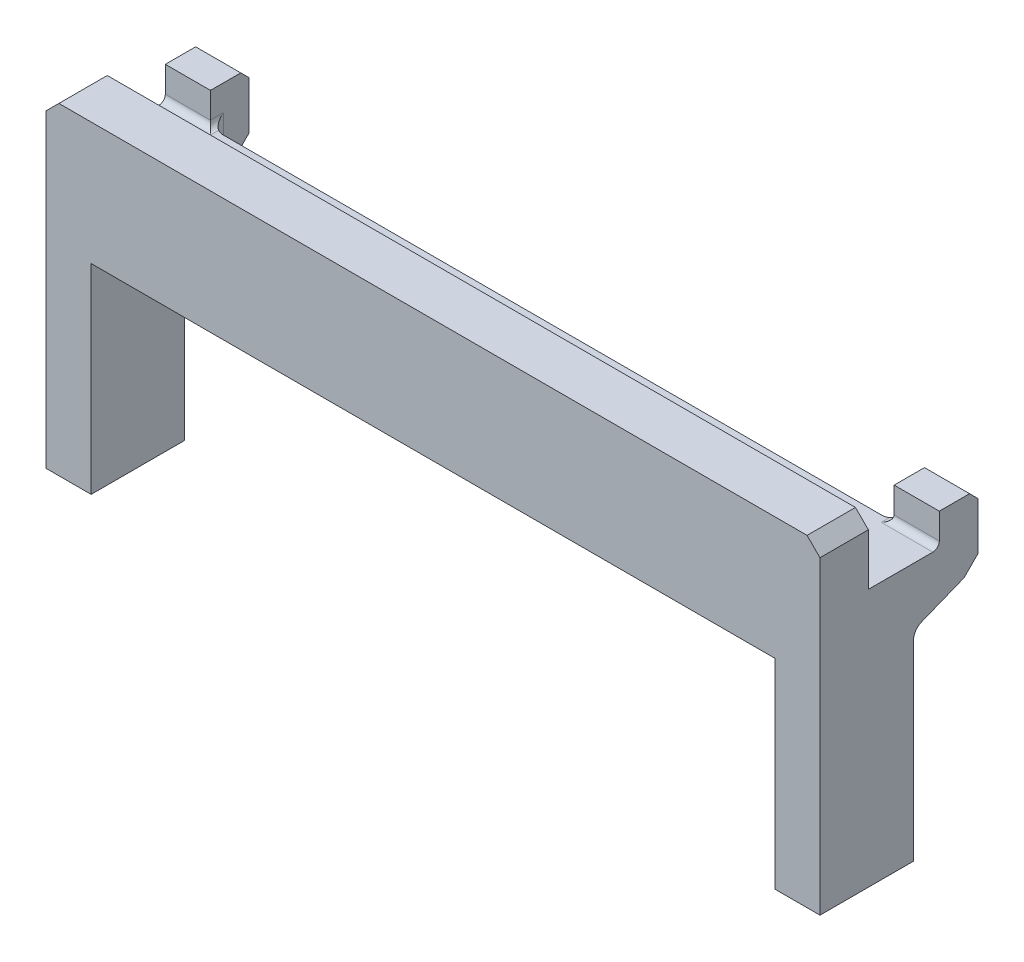
SolidWorks part; units mm, degrees
material "PLA2"
ref_plane "Front Plane" through (0, 0, 0) normal (0, 0, 1) x (1, 0, 0)
ref_plane "Top Plane" through (0, 0, 0) normal (0, 1, 0) x (1, 0, 0)
ref_plane "Right Plane" through (0, 0, 0) normal (1, 0, 0) x (0, 0, -1)
sketch "Sketch1" plane through (0, 0, 0) normal (1, 0, 0) x (0, 0, -1)
  line L0 (0, 0) -> (0, 12.7)
  line L1 (0, 12.7) -> (-9.525, 12.7)
  line L2 (-9.525, 12.7) -> (-9.525, -50.8)
  line L3 (-9.525, -50.8) -> (8.89, -50.8)
  line L4 (8.89, -50.8) -> (8.89, 0)
  line L5 (8.89, 0) -> (0, 0)
  dimension "D1" = 12.7
  dimension "D2" = 8.89
  dimension "D3" = 50.8
  dimension "D4" = 9.525
extrude "Boss-Extrude1" add sketch "Sketch1" along normal mid plane 152.4
sketch "Sketch4" plane through (76.2, 0, 0) normal (1, 0, 0) x (0, 0, -1)
  line L0 (8.89, 0) -> (21.59, 0)
  line L1 (21.59, 0) -> (21.59, -6.35)
  line L2 (21.59, -6.35) -> (8.89, -11.43)
  line L3 (8.89, -50.8) -> (8.89, 0) construction
  line L4 (8.89, -11.43) -> (8.89, 0)
  line L5 (0, 0) -> (0, 12.7) construction
  dimension "D1" = 11.43
  dimension "D2" = 6.35
  dimension "D3" = 21.59
extrude "Boss-Extrude3" add sketch "Sketch4" against normal up to surface (152.4 mm away) up to face at (-76.2, -12.7, 0.2117)
sketch "Sketch2" plane through (0, 0, -8.89) normal (0, 0, -1) x (-1, 0, 0)
  line L0 (0, -50.8) -> (0, 12.7) construction
  line L1 (-76.2, -50.8) -> (76.2, -50.8) construction
  line L2 (-76.2, 12.7) -> (76.2, 12.7) construction
  line L3 (67.31, -11.43) -> (-67.31, -11.43)
  line L4 (-67.31, -11.43) -> (-67.31, -50.8)
  line L5 (-67.31, -50.8) -> (67.31, -50.8)
  line L6 (67.31, -11.43) -> (67.31, -50.8)
  line L7 (-76.2, -50.8) -> (-76.2, -11.43) construction
  line L9 (76.2, -11.43) -> (-76.2, -11.43) construction
  point P11 (0, -11.43)
  point P13 (0, 0)
  dimension "D1" = 8.89
extrude "Cut-Extrude1" cut sketch "Sketch2" against normal through all
chamfer "Chamfer1" distance 2.54 angle 45 2 edges at (-76.2, 12.7, 4.7625) (76.2, 12.7, 4.7625)
ref_plane "Plane1" through (71.755, 0, 0) normal (1, 0, 0) x (0, 0, -1)
ref_plane "Plane2" through (-71.755, 0, 0) normal (1, 0, 0) x (0, 0, -1)
ref_plane "Plane3" through (0, 0, 0.3175) normal (0, 0, 1) x (1, 0, 0)
sketch "Sketch5" plane through (76.2, 0, 0) normal (1, 0, 0) x (0, 0, -1)
  line L0 (21.59, 0) -> (21.59, 6.35)
  line L1 (21.59, 6.35) -> (13.97, 6.35)
  line L2 (13.97, 6.35) -> (13.97, 0)
  line L3 (21.59, 0) -> (0, 0) construction
  line L4 (13.97, 0) -> (21.59, 0)
  line L5 (0, 0) -> (0, 10.16) construction
  dimension "D1" = 13.97
  dimension "D2" = 6.35
extrude "Boss-Extrude4" add sketch "Sketch5" against normal blind 8.89
mirror "Mirror1" about plane through (0, 0, 0) normal (1, 0, 0) of "Boss-Extrude4"
sketch "Sketch6" plane through (0, 0, 0) normal (0, 1, 0) x (1, 0, 0)
  line L0 (-67.31, 21.59) -> (67.31, 21.59)
  line L1 (67.31, 21.59) -> (67.31, 13.97)
  line L2 (67.31, 13.97) -> (-67.31, 13.97)
  line L3 (-67.31, 13.97) -> (-67.31, 21.59)
extrude "Cut-Extrude2" cut sketch "Sketch6" against normal through all
fillet "Fillet1" radius 2.54 4 edges at (67.31, -4.699, -13.97) (-67.31, -4.699, -13.97) (-71.755, -11.43, -8.89) (71.755, -11.43, -8.89)
fillet "Fillet2" radius 1.27 4 edges at (71.755, 0, -13.97) (67.31, 0, -15.24) (-71.755, 0, -13.97) (-67.31, 0, -15.24)
chamfer "Chamfer2" distance 1.651 angle 45 4 edges at (-71.755, -6.35, -21.59) (71.755, 6.35, -21.59) (-71.755, 6.35, -21.59) (71.755, -6.35, -21.59)
